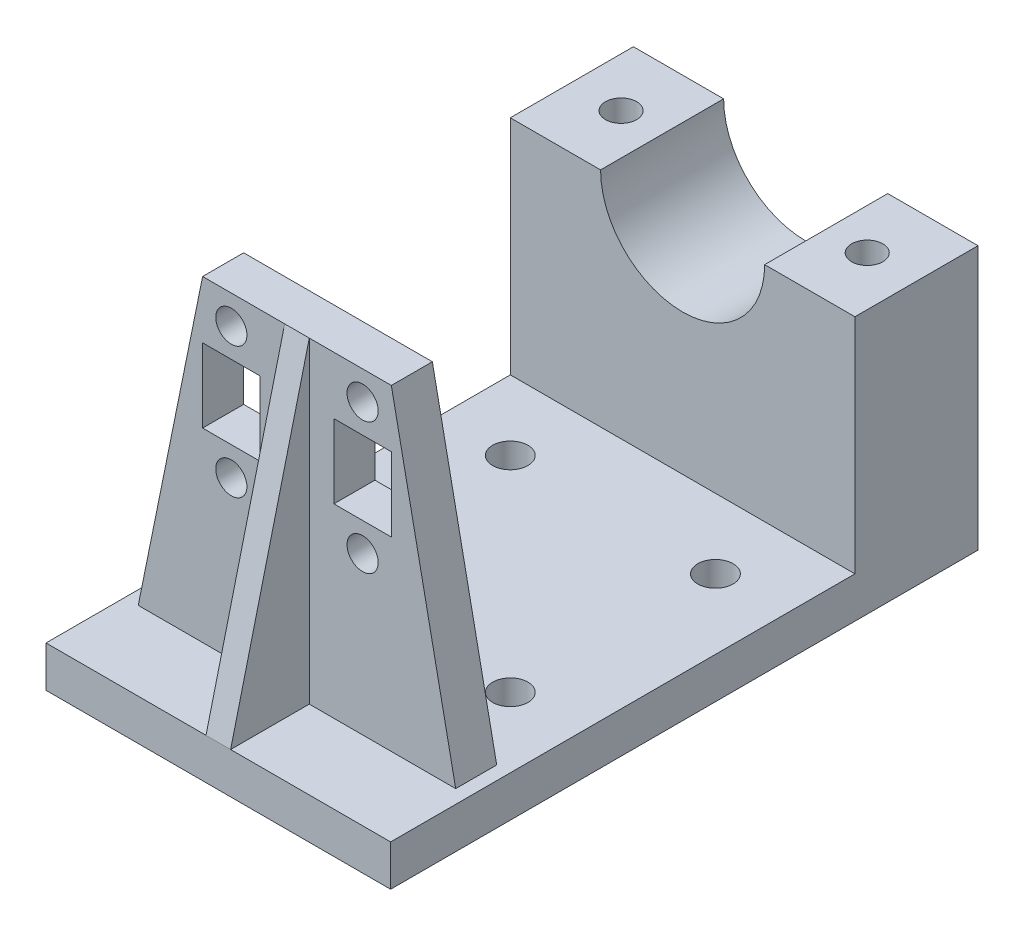
SolidWorks part; units mm, degrees
material "ABS"
ref_plane "Front Plane" through (0, 0, 0) normal (0, 0, 1) x (1, 0, 0)
ref_plane "Top Plane" through (0, 0, 0) normal (0, 1, 0) x (1, 0, 0)
ref_plane "Right Plane" through (0, 0, 0) normal (1, 0, 0) x (0, 0, -1)
sketch "Mouting Mount Sketch" plane through (0, 0, 0) normal (0, 0, 1) x (1, 0, 0)
  line L1 (25, -55) -> (-25, -55)
  line L2 (25, -55) -> (25, 0)
  line L3 (25, 0) -> (-25, 0)
  line L4 (-25, -55) -> (-25, 0)
  line L5 (25, -55) -> (-25, 0) construction
  line L6 (25, 0) -> (-25, -55) construction
  circle A0 centre (0, 0) radius 10
  point P3 (0, -27.5)
  dimension "D1" = 20
  dimension "D2" = 50
  dimension "D3" = 55
extrude "Motor Mount Solid" add sketch "Mouting Mount Sketch" along normal mid plane 15 contours A0 L3 L4 L1 L2
sketch "Encoder Distance Sketch" plane through (0, -55, 0) normal (0, -1, 0) x (1, 0, 0)
  line L0 (25, 7.5) -> (25, -7.5) construction
  line L1 (-25, 7.5) -> (25, 7.5)
  line L2 (-25, 7.5) -> (-25, 49.5)
  line L3 (-25, 49.5) -> (25, 49.5)
  line L4 (25, 7.5) -> (25, 49.5)
  line L5 (-25, -7.5) -> (25, -7.5) construction
  line L6 (-25, -7.5) -> (-25, 54.5) construction
  line L7 (-25, 54.5) -> (25, 54.5) construction
  line L8 (25, -7.5) -> (25, 54.5) construction
  line M9 (-25, -7.5) -> (25, -7.5)
  line M10 (25, -7.5) -> (25, 7.5)
  line M11 (25, 7.5) -> (-25, 7.5)
  line M12 (-25, 7.5) -> (-25, -7.5)
  dimension "D1" = 42
  dimension "D2" = 5
extrude "Encoder Distance Solid" add sketch "Encoder Distance Sketch" along normal blind 5 contours M12 M9 M10 M11 | L4 L3 L2 M11 | L3 L8 L7 L6
sketch "Encoder Mount Sketch" plane through (0, 0, 49.5) normal (0, 0, 1) x (1, 0, 0)
  line L0 (-25, -60) -> (-25, -55)
  line L1 (-8, -8) -> (8, -8) construction
  line L2 (-8, -8) -> (-8, 8) construction
  line L3 (-8, 8) -> (8, 8) construction
  line L4 (8, -8) -> (8, 8) construction
  line L5 (-8, -8) -> (8, 8) construction
  line L6 (-8, 8) -> (8, -8) construction
  line L7 (-11.5, -11.5) -> (11.5, -11.5) construction
  line L8 (-11.5, -11.5) -> (-11.5, 11.5) construction
  line L9 (-11.5, 11.5) -> (11.5, 11.5)
  line L10 (11.5, -11.5) -> (11.5, 11.5) construction
  line L11 (-11.5, -11.5) -> (11.5, 11.5) construction
  line L12 (-11.5, 11.5) -> (11.5, -11.5) construction
  line L13 (-11.5, 4.5) -> (-4.5, 4.5)
  line L14 (-11.5, 4.5) -> (-11.5, -4.5)
  line L15 (-11.5, -4.5) -> (-4.5, -4.5)
  line L16 (-4.5, 4.5) -> (-4.5, -4.5)
  line L17 (-11.5, 4.5) -> (-4.5, -4.5) construction
  line L18 (-11.5, -4.5) -> (-4.5, 4.5) construction
  line L19 (4.5, 4.5) -> (11.5, 4.5)
  line L20 (4.5, 4.5) -> (4.5, -4.5)
  line L21 (4.5, -4.5) -> (11.5, -4.5)
  line L22 (11.5, 4.5) -> (11.5, -4.5)
  line L23 (4.5, 4.5) -> (11.5, -4.5) construction
  line L24 (4.5, -4.5) -> (11.5, 4.5) construction
  line L25 (-25, -55) -> (-11.5, 11.5)
  line L26 (-25, -60) -> (25, -60)
  line L27 (25, -60) -> (25, -55)
  line L28 (25, -55) -> (11.5, 11.5)
  circle A0 centre (-8, 8) radius 1.9
  circle A1 centre (8, 8) radius 1.9
  circle A2 centre (-8, -8) radius 1.9
  circle A3 centre (8, -8) radius 1.9
  circle A4 centre (8, 8) radius 3.5 construction
  circle A5 centre (-8, 8) radius 3.5 construction
  circle A6 centre (-8, -8) radius 3.5 construction
  circle A7 centre (8, -8) radius 3.5 construction
  point P0 (0, 0)
  point P14 (0, 0)
  point P19 (-8, 0)
  point P24 (8, 0)
  dimension "D2" = 3.8
  dimension "D3" = 7
  dimension "D1" = 16
extrude "Encoder Mount Solid" add sketch "Encoder Mount Sketch" along normal blind 5
sketch "Motor Clamp Mounting Holes Sketch" plane through (0, 0, 0) normal (0, 1, 0) x (1, 0, 0)
  line L0 (-15, 0) -> (15, 0) construction
  circle A0 centre (-15, 0) radius 1.9
  circle A1 centre (15, 0) radius 1.9
  point P4 (0, 0)
  dimension "D2" = 3.8
  dimension "D1" = 30
extrude "Motor Clamp Mounting Holes Cut" cut sketch "Motor Clamp Mounting Holes Sketch" against normal blind 16
sketch "Gusset Plate Sketch" plane through (0, 0, 54.5) normal (0, 0, 1) x (1, 0, 0)
  line L1 (-25, -55) -> (25, -55)
  line L2 (-25, -55) -> (-25, -60)
  line L3 (-25, -60) -> (25, -60)
  line L4 (25, -55) -> (25, -60)
extrude "Gusset Plate Solid" add sketch "Gusset Plate Sketch" along normal blind 16.5
sketch "Gusset Sketch" plane through (0, 0, 0) normal (1, 0, 0) x (0, 0, -1)
  line L0 (-54.5, 11.5) -> (-71, -55)
  line L1 (-71, -55) -> (-54.5, -55)
  line L2 (-54.5, -55) -> (-54.5, 11.5)
extrude "Gusset Solid" add sketch "Gusset Sketch" along normal mid plane 3
sketch "Mounting Plate Sketch" plane through (0, -55, 0) normal (0, 1, 0) x (1, 0, 0)
  line L0 (25, -7.5) -> (25, -49.5) construction
  line L1 (-25, -71) -> (25, -71)
  line L2 (-25, -71) -> (-25, 21)
  line L3 (-25, 21) -> (25, 21)
  line L4 (25, -71) -> (25, 21)
  line L5 (-19, -65) -> (19, -65) construction
  line L6 (-19, 15) -> (19, 15) construction
  circle A0 centre (-19, -65) radius 2.65
  circle A1 centre (19, -65) radius 6 construction
  circle A2 centre (19, -65) radius 2.65
  circle A3 centre (-19, -65) radius 6 construction
  circle A4 centre (-19, 15) radius 6 construction
  circle A5 centre (19, 15) radius 6 construction
  circle A6 centre (-19, 15) radius 2.65
  circle A7 centre (19, 15) radius 2.65
  point P10 (0, -65)
  point P18 (0, 15)
  dimension "D1" = 12
  dimension "D2" = 5.3
  dimension "D3" = 80
extrude "Mounting Plate Solid" add sketch "Mounting Plate Sketch" against normal up to surface (5 mm away) up to face at (0, -60, 31.75)
sketch "Mounting Hole Sketch" plane through (0, -55, 0) normal (0, 1, 0) x (1, 0, 0)
  line L0 (25, 21) -> (25, -71) construction
  line L3 (25, -25) -> (-25, -25) construction
  line L4 (-25, -49.5) -> (-25, -7.5) construction
  circle A0 centre (-19, 15) radius 2.65
  circle A1 centre (19, 15) radius 2.65
  circle A3 centre (19, -65) radius 2.65
  circle A4 centre (-19, -65) radius 2.65
  circle A5 centre (-19, 15) radius 2.65 construction
extrude "Mounting Holes Cut" cut sketch "Mounting Hole Sketch" against normal through all both and the other way through all contours A3 | A4 | A1 | A0
sketch "Mounting Plate Trim Sketch" plane through (0, -55, 0) normal (0, 1, 0) x (1, 0, 0)
  line L1 (-25, 21) -> (25, 21)
  line L2 (-25, 21) -> (-25, 7.5)
  line L3 (-25, 7.5) -> (25, 7.5)
  line L4 (25, 21) -> (25, 7.5)
  line L5 (-25, -7.5) -> (25, -7.5)
  line L6 (-25, -7.5) -> (-25, -49.5)
  line L7 (-25, -49.5) -> (25, -49.5)
  line L8 (25, -7.5) -> (25, -49.5)
  line L9 (1.5, -54.5) -> (25, -54.5)
  line L10 (1.5, -54.5) -> (1.5, -71)
  line L11 (1.5, -71) -> (25, -71)
  line L12 (25, -54.5) -> (25, -71)
  line L13 (-1.5, -54.5) -> (-25, -54.5)
  line L14 (-1.5, -54.5) -> (-1.5, -71)
  line L15 (-1.5, -71) -> (-25, -71)
  line L16 (-25, -54.5) -> (-25, -71)
extrude "Mounting Plate Trim Cut" cut sketch "Mounting Plate Trim Sketch" against normal blind 2
sketch "Sketch2" plane through (0, 0, -7.5) normal (0, 0, -1) x (-1, 0, 0)
  line L1 (-21, -27.1363) -> (21, -27.1363)
  line L2 (-21, -27.1363) -> (-21, 27.1363)
  line L3 (-21, 27.1363) -> (21, 27.1363)
  line L4 (21, -27.1363) -> (21, 27.1363)
  line L5 (-21, -27.1363) -> (21, 27.1363) construction
  line L6 (-21, 27.1363) -> (21, -27.1363) construction
  line L7 (25, 60) -> (-25, 60)
  line L8 (25, 60) -> (25, -60)
  line L9 (25, -60) -> (-25, -60)
  line L10 (-25, 60) -> (-25, -60)
  line L11 (25, 60) -> (-25, -60) construction
  line L12 (25, -60) -> (-25, 60) construction
  point P0 (0, 0)
  point P7 (0, 0)
  dimension "D1" = 42
  dimension "D2" = 27.1363
extrude "Cut-Extrude1" cut sketch "Sketch2" against normal through all both and the other way through all
sketch "Sketch3" plane through (0, -27.1363, 0) normal (0, -1, 0) x (1, 0, 0)
  line L0 (21, 7.5) -> (21, -7.5) construction
  line L1 (-21, -7.5) -> (21, -7.5)
  line L2 (-21, -7.5) -> (-21, 64.0865)
  line L3 (-21, 64.0865) -> (21, 64.0865)
  line L4 (21, -7.5) -> (21, 64.0865)
  line L5 (-21, -7.5) -> (21, -7.5) construction
  line L6 (1.5, 64.0865) -> (-1.5, 64.0865) construction
  point P5 (21, -7.5)
  point P10 (21, 59.7931)
extrude "Boss-Extrude1" add sketch "Sketch3" along normal blind 5
sketch "Sketch4" plane through (0, -27.1363, 0) normal (0, 1, 0) x (1, 0, 0)
  line L0 (21, -7.5) -> (21, -64.0865) construction
  line L1 (-21, -7.5) -> (21, -7.5) construction
  line L2 (-21, -7.5) -> (-21, -49.5) construction
  line L3 (-21, -49.5) -> (21, -49.5) construction
  line L4 (21, -7.5) -> (21, -49.5) construction
  line L5 (19.3435, -49.5) -> (-19.3435, -49.5) construction
  line L6 (-21, -7.5) -> (21, -49.5) construction
  line L8 (-12.5, -41) -> (12.5, -41) construction
  line L9 (-12.5, -41) -> (-12.5, -16) construction
  line L10 (-12.5, -16) -> (12.5, -16) construction
  line L11 (12.5, -41) -> (12.5, -16) construction
  line L12 (-12.5, -41) -> (12.5, -16) construction
  line L13 (-12.5, -16) -> (12.5, -41) construction
  circle A0 centre (12.5, -16) radius 5 construction
  circle A1 centre (-12.5, -16) radius 5 construction
  circle A2 centre (-12.5, -41) radius 5 construction
  circle A3 centre (12.5, -41) radius 5 construction
  circle A4 centre (-12.5, -16) radius 2.15
  circle A5 centre (12.5, -16) radius 2.15
  circle A6 centre (-12.5, -41) radius 2.15
  circle A7 centre (12.5, -41) radius 2.15
  point P9 (0, -28.5)
  dimension "D1" = 10
  dimension "D4" = 4.3
  dimension "D2" = 25
  dimension "D3" = 25
extrude "Cut-Extrude2" cut sketch "Sketch4" against normal through all both and the other way through all contours A5 | A4
